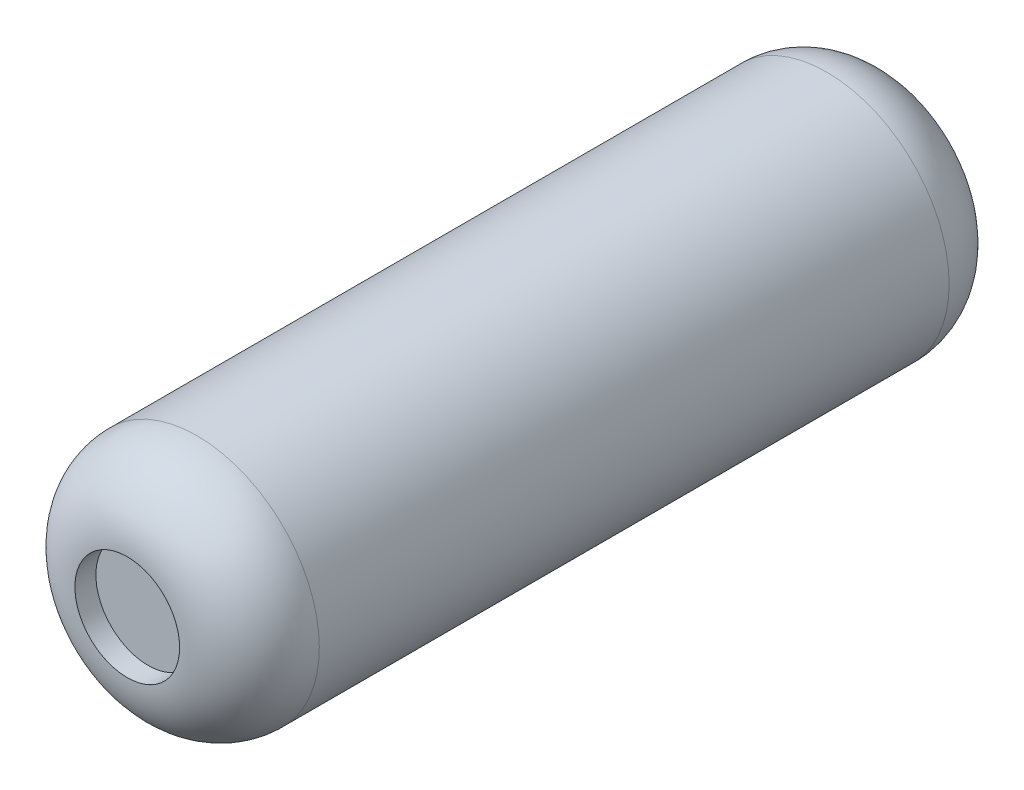
SolidWorks part; units mm, degrees
ref_plane "Front" through (0, 0, 0) normal (0, 0, 1) x (1, 0, 0)
ref_plane "Top" through (0, 0, 0) normal (0, 1, 0) x (1, 0, 0)
ref_plane "Right" through (0, 0, 0) normal (1, 0, 0) x (0, 0, -1)
sketch "Sketch1" plane through (0, 0, 0) normal (0, 0, 1) x (1, 0, 0)
  circle A0 centre (0, 0) radius 44.4904
  dimension "D1" = 88.9809
extrude "Extrude1" add sketch "Sketch1" along normal blind 280
sketch "Sketch2" plane through (0, 0, 280) normal (0, 0, 1) x (1, 0, 0)
  point P0 (0, 0)
fillet "Fillet1" radius 25.4 2 edges at (44.4904, 0, 0) (44.4904, 0, 280)
sketch "Sketch3" plane through (0, 0, 0) normal (0, 0, -1) x (-1, 0, 0)
  line L1 (-10, 5) -> (10, 5)
  line L2 (-10, 5) -> (-10, -5)
  line L3 (-10, -5) -> (10, -5)
  line L4 (10, 5) -> (10, -5)
  line L5 (-10, 5) -> (10, -5) construction
  line L6 (-10, -5) -> (10, 5) construction
  point P0 (0, 0)
  dimension "D1" = 20
  dimension "D2" = 10
extrude "Cut-Extrude1" cut sketch "Sketch3" against normal blind 7.62
sketch "Sketch4" plane through (0, 0, 280) normal (0, 0, 1) x (1, 0, 0)
  circle A0 centre (0, 0) radius 19.05
  dimension "D1" = 38.1
extrude "Cut-Extrude2" cut sketch "Sketch4" against normal blind 7.62
